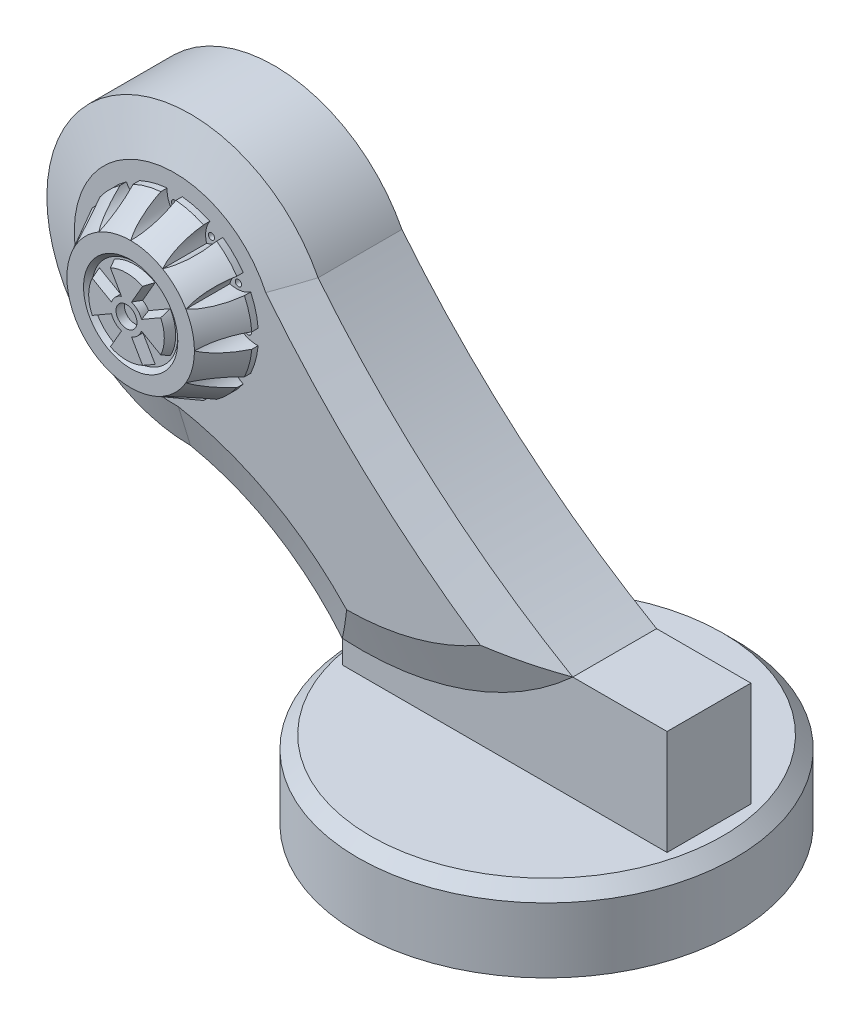
SolidWorks part; units mm, degrees
ref_plane "Front Plane" through (0, 0, 0) normal (0, 0, 1) x (1, 0, 0)
ref_plane "Top Plane" through (0, 0, 0) normal (0, 1, 0) x (1, 0, 0)
ref_plane "Right Plane" through (0, 0, 0) normal (1, 0, 0) x (0, 0, -1)
sketch "Sketch1" plane through (0, 0, 0) normal (0, 1, 0) x (1, 0, 0)
  circle A0 centre (0, 0) radius 90
  dimension "D1" = 180
extrude "Boss-Extrude1" add sketch "Sketch1" along normal blind 37
chamfer "Chamfer1" distance 6 angle 45 1 edges at (0, 37, 90)
sketch "Sketch2" plane through (0, 37, 0) normal (0, 1, 0) x (1, 0, 0)
  line L1 (-77.5, -20) -> (77.5, -20)
  line L2 (-77.5, -20) -> (-77.5, 20)
  line L3 (-77.5, 20) -> (77.5, 20)
  line L4 (77.5, -20) -> (77.5, 20)
  line L5 (-77.5, -20) -> (77.5, 20) construction
  line L6 (-77.5, 20) -> (77.5, -20) construction
  point P0 (0, 0)
  dimension "D1" = 155
  dimension "D2" = 40
extrude "Boss-Extrude2" add sketch "Sketch2" along normal blind 50
sketch "Sketch4" plane through (0, 0, 20) normal (0, 0, 1) x (1, 0, 0)
  line L0 (-77.5, 87) -> (32.5, 87)
  line L1 (-77.5, 87) -> (77.5, 87) construction
  line L3 (-77.5, 87) -> (-77.5, 48)
  line L4 (-77.5, 87) -> (-77.5, 37) construction
  arc A0 (-77.5, 48) -> (32.5, 87) centre (-68.6761, 197.7402) ccw
  dimension "D3" = 150
  dimension "D1" = 39
  dimension "D2" = 110
extrude "Cut-Extrude1" cut sketch "Sketch4" against normal through all
sketch "Sketch5" plane through (0, 0, 0) normal (0, 0, 1) x (1, 0, 0)
  arc A0 (-89.0396, 191.2422) -> (-150, 91.5) centre (-150, 160) ccw
  arc A1 (-77.5, 48) -> (-150, 91.5) centre (-174.2724, -31.1207) ccw
  arc A2 (32.5, 87) -> (-89.0396, 191.2422) centre (253.4003, 467.53) cw
  arc A3 (-77.5, 48) -> (32.5, 87) centre (-68.6761, 197.7402) ccw construction
  arc A4 (-77.5, 48) -> (32.5, 87) centre (-68.6761, 197.7402) ccw
  dimension "D3" = 137
  dimension "D4" = 440
  dimension "D5" = 125
  dimension "D1" = 150
  dimension "D2" = 160
extrude "Boss-Extrude4" add sketch "Sketch5" along normal mid plane 40 separate body
sketch "Sketch7" plane through (0, 0, 20) normal (0, 0, 1) x (1, 0, 0)
  arc A4 (-77.5, 48) -> (32.5, 87) centre (-68.6761, 197.7402) ccw
  arc A5 (-89.0396, 191.2422) -> (32.5, 87) centre (253.4003, 467.53) ccw
  arc A6 (-89.0396, 191.2422) -> (-150, 91.5) centre (-150, 160) ccw
  arc A7 (-77.5, 48) -> (-150, 91.5) centre (-174.2724, -31.1207) ccw
  arc A8 (-77.5, 48) -> (32.5, 87) centre (-68.6761, 197.7402) ccw
  arc A9 (-89.0396, 191.2422) -> (32.5, 87) centre (253.4003, 467.53) ccw
  arc A10 (-89.0396, 191.2422) -> (-150, 91.5) centre (-150, 160) ccw
  arc A11 (-77.5, 48) -> (-150, 91.5) centre (-174.2724, -31.1207) ccw
  dimension "D1" = 0
extrude "Boss-Extrude5" add sketch "Sketch7" along normal blind 7.5 draft 70
sketch "Sketch8" plane through (0, 0, 27.5) normal (0, 0, 1) x (1, 0, 0)
  circle A0 centre (-150, 160) radius 40
  dimension "D1" = 80
extrude "Boss-Extrude6" add sketch "Sketch8" along normal blind 3
sketch "Sketch9" plane through (0, 0, 30.5) normal (0, 0, 1) x (1, 0, 0)
  circle A1 centre (-150, 160) radius 40
  circle A2 centre (-150, 160) radius 40
  dimension "D1" = 0
extrude "Boss-Extrude7" add sketch "Sketch9" along normal blind 18 draft 28
sketch "Sketch10" plane through (0, 0, 48.5) normal (0, 0, 1) x (1, 0, 0)
  line L0 (-150, 160) -> (-150, 256.4022) construction
  circle A0 centre (-150, 160) radius 40 construction
  arc A1 (-146.4005, 199.8377) -> (-153.5995, 199.8377) centre (-150, 160) ccw
  circle A2 centre (-150, 160) radius 30.4292 construction
  arc A4 (-150, 190.4292) -> (-146.4005, 199.8377) centre (-158.373, 199.0254) ccw
  arc A5 (-150, 190.4292) -> (-153.5995, 199.8377) centre (-141.627, 199.0254) cw
  dimension "D1" = 12
extrude "Cut-Extrude2" cut sketch "Sketch10" against normal up to surface (21 mm away) up to face at (-110, 160, 27.5)
sketch "Sketch11" plane through (0, 0, 27.5) normal (0, 0, 1) x (1, 0, 0)
  line L0 (-153.5995, 199.8377) -> (-146.4005, 199.8377) construction
  line L1 (-150, 199.8377) -> (-150, 190.4292) construction
  circle A0 centre (-150, 195.1335) radius 1.5
  dimension "D1" = 3
extrude "Cut-Extrude3" cut sketch "Sketch11" against normal blind 5
pattern_circular "CirPattern1" count 12 over 360 about axis through (-150, 160, 0) along (0, 0, 1) of "Cut-Extrude2", "Cut-Extrude3"
sketch "Sketch12" plane through (0, 0, 48.5) normal (0, 0, 1) x (1, 0, 0)
  circle A0 centre (-150, 160) radius 22.5
  dimension "D1" = 45
extrude "Cut-Extrude4" cut sketch "Sketch12" against normal blind 2 draft 45
sketch "Sketch13" plane through (0, 0, 46.5) normal (0, 0, 1) x (1, 0, 0)
  line L0 (-150, 160) -> (-150, 221.257) construction
  line L1 (-159.7035, 176.9143) -> (-153, 165.3036)
  line L2 (-140.2965, 176.9143) -> (-147, 165.3036)
  arc A0 (-147, 165.3036) -> (-153, 165.3036) centre (-150, 160) ccw
  arc A1 (-140.2965, 176.9143) -> (-159.7035, 176.9143) centre (-150, 160) ccw
  dimension "D1" = 12.1865
  dimension "D2" = 39
  dimension "D3" = 30
  dimension "D4" = 3
extrude "Boss-Extrude9" add sketch "Sketch13" along normal blind 4 draft 20
pattern_circular "CirPattern2" count 4 over 360 about axis through (-150, 160, 0) along (0, 0, 1) of "Boss-Extrude9"
sketch "Sketch14" plane through (0, 0, 46.5) normal (0, 0, 1) x (1, 0, 0)
  circle A0 centre (-150, 160) radius 7.5491
extrude "Boss-Extrude10" add sketch "Sketch14" along normal up to surface (4 mm away) up to face at (-150, 172.2701, 50.5)
sketch "Sketch15" plane through (0, 0, 50.5) normal (0, 0, 1) x (1, 0, 0)
  circle A0 centre (-150, 160) radius 5
  dimension "D1" = 10
extrude "Cut-Extrude5" cut sketch "Sketch15" against normal up to surface (4 mm away) up to face at (-129.5, 160, 46.5)
sketch "Sketch16" plane through (0, 0, -20) normal (0, 0, -1) x (-1, 0, 0)
  circle A0 centre (150, 160) radius 15
  dimension "D1" = 30
extrude "Cut-Extrude6" cut sketch "Sketch16" against normal blind 20
sketch "Sketch17" plane through (0, 0, 0) normal (0, -1, 0) x (1, 0, 0)
  circle A0 centre (0, 0) radius 15
  dimension "D1" = 30
extrude "Cut-Extrude7" cut sketch "Sketch17" against normal blind 20
